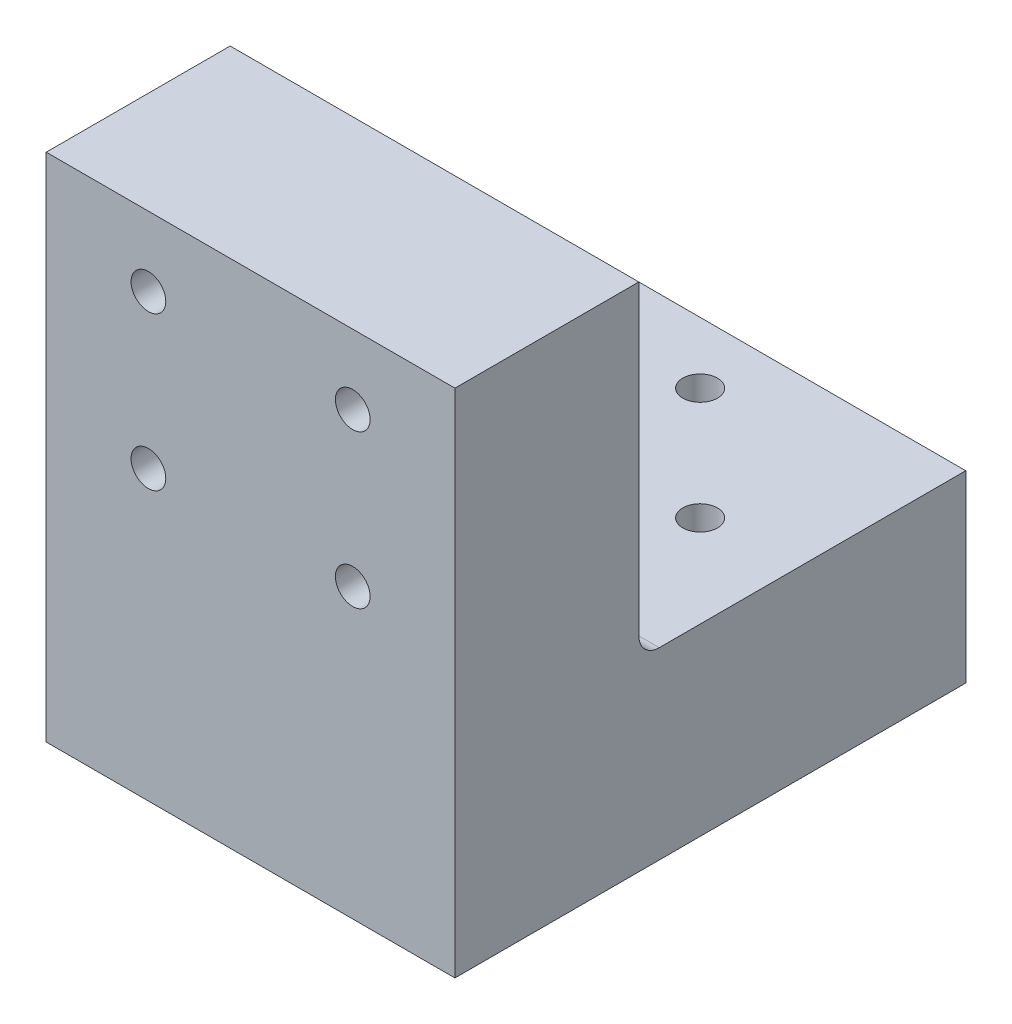
SolidWorks part; units mm, degrees
material "PLA"
ref_plane "Front Plane" through (0, 0, 0) normal (0, 0, 1) x (1, 0, 0)
ref_plane "Top Plane" through (0, 0, 0) normal (0, 1, 0) x (1, 0, 0)
ref_plane "Right Plane" through (0, 0, 0) normal (1, 0, 0) x (0, 0, -1)
sketch "Sketch3" plane through (0, 0, 0) normal (1, 0, 0) x (0, 0, -1)
  line L0 (0, -23.1861) -> (50, -23.1861)
  line L1 (50, -23.1861) -> (50, -5.1861)
  line L2 (0, -23.1861) -> (0, 26.8139)
  line L3 (0, 26.8139) -> (18, 26.8139)
  line L6 (18, 26.8139) -> (18, -3.1861)
  line L7 (20, -5.1861) -> (50, -5.1861)
  arc A0 (18, -3.1861) -> (20, -5.1861) centre (20, -3.1861) ccw
  point P8 (0, 0)
  point P9 (0, 0)
  dimension "D7" = 2
  dimension "D1" = 50
  dimension "D2" = 18
  dimension "D3" = 50
  dimension "D4" = 18
extrude "Boss-Extrude2" add sketch "Sketch3" along normal blind 40
sketch "Sketch6" plane through (0, -5.1861, 0) normal (0, 1, 0) x (1, 0, 0)
  line L0 (40, 50) -> (40, 20) construction
  line L3 (-22, 0) -> (22, 0) construction
  circle A0 centre (20, 33) radius 3.25
  circle A2 centre (20, 33) radius 11 construction
  circle A3 centre (9, 33) radius 1.7
  circle A4 centre (20, 44) radius 1.7
  circle A5 centre (31, 33) radius 1.7
  circle A6 centre (20, 22) radius 1.7
  point P13 (36.5163, 33)
  point P14 (3.8471, 33)
  point P15 (0, 0)
  point P16 (0, 0)
  point P17 (21.0288, 47.0884)
  point P20 (20, 17.9372)
  point P21 (0, 0)
  point P22 (20, 47.0067)
  point P23 (0, 0)
  point P24 (0, 0)
  point P25 (0, 0)
  dimension "D1" = 6.5
  dimension "D2" = 20
  dimension "D3" = 33
extrude "Cut-Extrude1" cut sketch "Sketch6" against normal through all
sketch "Sketch7" plane through (0, 0, -18) normal (0, 0, -1) x (-1, 0, 0)
  circle A0 centre (-30, 20) radius 1.7
  circle A1 centre (-10, 20) radius 1.7
  circle A2 centre (-30, 5) radius 1.7
  circle A3 centre (-10, 5) radius 1.7
  point P8 (0, 0)
  point P9 (-9.0525, 18.6464)
extrude "Cut-Extrude2" cut sketch "Sketch7" against normal through all
